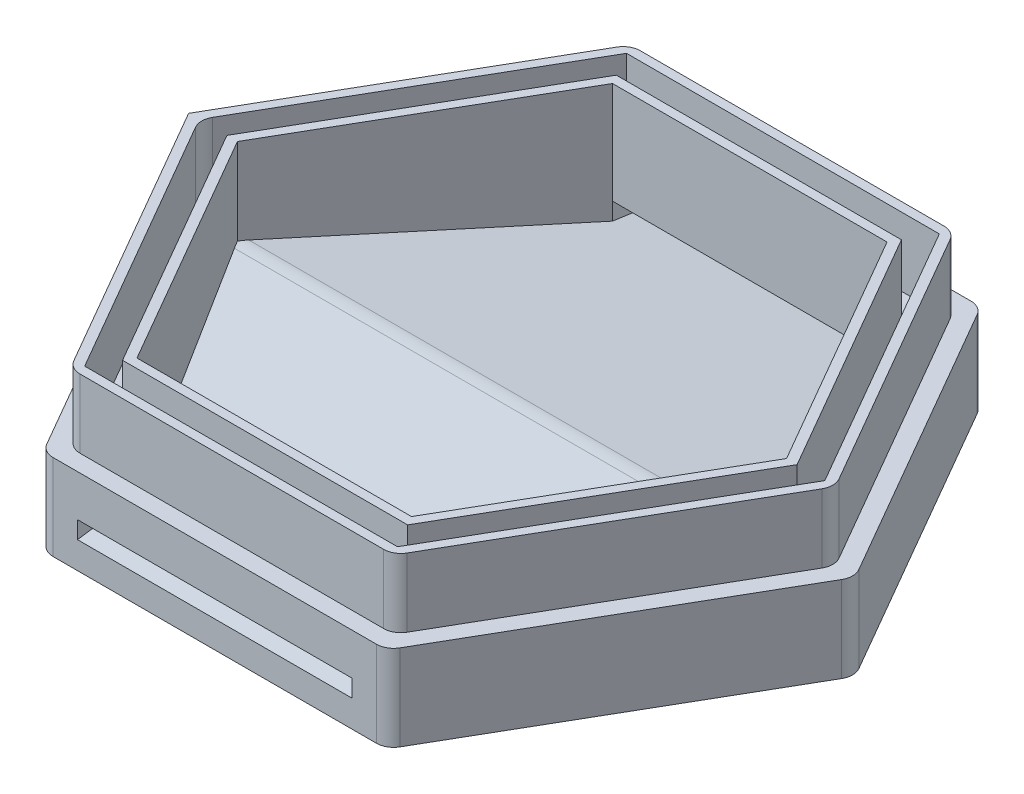
SolidWorks part; units mm, degrees
ref_plane "Front Plane" through (0, 0, 0) normal (0, 0, 1) x (1, 0, 0)
ref_plane "Top Plane" through (0, 0, 0) normal (0, 1, 0) x (1, 0, 0)
ref_plane "Right Plane" through (0, 0, 0) normal (1, 0, 0) x (0, 0, -1)
sketch "Sketch1" plane through (0, 0, 0) normal (0, 1, 0) x (1, 0, 0)
  line L1 (0, 0) -> (-50, 86.6025)
  line L2 (-50, 86.6025) -> (-150, 86.6025)
  line L3 (-150, 86.6025) -> (-200, 0)
  line L4 (-200, 0) -> (-150, -86.6025)
  line L5 (-150, -86.6025) -> (-50, -86.6025)
  line L6 (-50, -86.6025) -> (0, 0)
  dimension "200" = 200
extrude "Boss-Extrude1" add sketch "Sketch1" along normal blind 25
sketch "Sketch6" plane through (0, 25, 0) normal (0, 1, 0) x (1, 0, 0)
  line L0 (-100, -86.6025) -> (-100, 86.6025) construction
  line L3 (0, 0) -> (-200, 0) construction
  line L4 (-150, -86.6025) -> (-50, -86.6025) construction
  line L5 (-50, 86.6025) -> (-150, 86.6025) construction
  line L7 (-180, 0) -> (-140, -69.282)
  line L8 (-140, -69.282) -> (-60, -69.282)
  line L9 (-60, -69.282) -> (-20, 0)
  line L10 (-20, 0) -> (-60, 69.282)
  line L11 (-60, 69.282) -> (-140, 69.282)
  line L12 (-140, 69.282) -> (-180, 0)
  circle A0 centre (-100, 0) radius 69.282 construction
  dimension "D1" = 160
extrude "Cut-Extrude1" cut sketch "Sketch6" against normal blind 5
ref_plane "Plane3" through (0, 36.0941, 6.3644) normal (0, 0.9848, 0.1736) x (1, 0, 0)
sketch "Sketch10" plane through (0, 20, 0) normal (0, 1, 0) x (1, 0, 0)
  line L0 (-100, 69.282) -> (-100, -69.282) construction
  line L1 (-60, 69.282) -> (-140, 69.282) construction
  line L2 (-140, -69.282) -> (-60, -69.282) construction
  line L3 (-180, 0) -> (-20, 0) construction
  line L4 (-60, -69.282) -> (-140, 69.282) construction
  line L5 (-40, 34.641) -> (-160, -34.641) construction
  line L6 (-20, 0) -> (-60, 69.282) construction
  line L7 (-180, 0) -> (-140, -69.282) construction
  line L8 (-140, -69.282) -> (-60, 69.282) construction
  line L9 (-40, -34.641) -> (-160, 34.641) construction
  line L10 (-60, -69.282) -> (-20, 0) construction
  line L11 (-140, 69.282) -> (-180, 0) construction
ref_plane "Plane10" through (-100, 0, 0) normal (1, 0, 0) x (0, 0, -1)
sketch "Sketch21" plane through (-100, 0, 0) normal (1, 0, 0) x (0, 0, -1)
  line L0 (69.282, 20) -> (69.282, 10.263)
  line L2 (69.282, 10.263) -> (0, 20)
  line L3 (0, 25) -> (0, 0) construction
  line L4 (0, 0) -> (0, 20) construction
  line L5 (0, 20) -> (69.282, 20)
  line L6 (69.282, 25) -> (69.282, 20) construction
  line L7 (0, 20) -> (69.282, 20) construction
  dimension "D1" = 8
extrude "Cut-Extrude7" cut sketch "Sketch21" along normal up to surface and the other way up to surface up to face at (-40, 22.5, -34.641) other way up to face at (-160, 22.5, -34.641)
sketch "Sketch22" plane through (-100, 0, 0) normal (1, 0, 0) x (0, 0, -1)
  line L0 (0, 20) -> (-69.282, 10.263)
  line L1 (-69.282, 10.263) -> (-69.282, 20)
  line L2 (-69.282, 20) -> (0, 20)
  line L3 (69.282, 25) -> (69.282, 10.263) construction
  line L4 (69.282, 10.263) -> (69.282, 25) construction
  line L5 (69.282, 10.263) -> (-69.282, 10.263) construction
  dimension "D1" = 8
extrude "Cut-Extrude8" cut sketch "Sketch22" along normal up to surface and the other way up to surface up to face at (-40, 22.5, 34.641) other way up to face at (-160, 22.5, 34.641)
sketch "Sketch23" plane through (-100, 0, 0) normal (1, 0, 0) x (0, 0, -1)
  line L0 (69.282, 10.263) -> (89.282, 7.4522)
  line L1 (89.282, 7.4522) -> (89.282, 12.5014)
  line L2 (89.282, 12.5014) -> (69.282, 15.3122)
  line L3 (69.282, 10.263) -> (69.282, 25) construction
  line L4 (0, 20) -> (69.282, 10.263) construction
  line L5 (69.282, 15.3122) -> (69.282, 10.263)
  line L6 (0, 25) -> (0, 38.3565) construction
  line L7 (-69.282, 15.3122) -> (-69.282, 10.263)
  line L8 (-89.282, 12.5014) -> (-69.282, 15.3122)
  line L9 (-89.282, 7.4522) -> (-89.282, 12.5014)
  line L10 (-69.282, 10.263) -> (-89.282, 7.4522)
  dimension "D1" = 5
  dimension "D2" = 20
extrude "Cut-Extrude9" cut sketch "Sketch23" against normal up to vertex (40 mm away) and the other way up to vertex (40 mm away)
fillet "Fillet2" radius 15 1 edges at (-100, 20, 0)
sketch "Sketch27" plane through (0, 25, 0) normal (0, 1, 0) x (1, 0, 0)
  line L0 (0, 0) -> (-200, 0) construction
  line L1 (-100, 86.6025) -> (-100, -86.6025) construction
  line L2 (-50, 86.6025) -> (-150, 86.6025) construction
  line L3 (-150, -86.6025) -> (-50, -86.6025) construction
  line L4 (-140, 69.282) -> (-180, 0) construction
  line L5 (-10, 0) -> (-55, 77.9423) construction
  line L6 (-55, 77.9423) -> (-145, 77.9423) construction
  line L7 (-145, 77.9423) -> (-190, 0) construction
  line L8 (-190, 0) -> (-145, -77.9423) construction
  line L9 (-145, -77.9423) -> (-55, -77.9423) construction
  line L10 (-55, -77.9423) -> (-10, 0) construction
  line L23 (-15.7735, 0) -> (-57.8868, 72.9423) construction
  line L24 (-57.8868, 72.9423) -> (-142.1132, 72.9423) construction
  line L25 (-142.1132, 72.9423) -> (-184.2265, 0) construction
  line L26 (-184.2265, 0) -> (-142.1132, -72.9423) construction
  line L27 (-142.1132, -72.9423) -> (-57.8868, -72.9423) construction
  line L28 (-57.8868, -72.9423) -> (-15.7735, 0) construction
  line L29 (-150, 86.6025) -> (-200, 0) construction
  line L30 (-178.7947, 2.0876) -> (-140, 69.282) construction
  line L32 (-16.9282, 0) -> (-58.4641, 71.9423)
  line L33 (-58.4641, 71.9423) -> (-141.5359, 71.9423)
  line L34 (-141.5359, 71.9423) -> (-183.0718, 0)
  line L35 (-183.0718, 0) -> (-141.5359, -71.9423)
  line L36 (-141.5359, -71.9423) -> (-58.4641, -71.9423)
  line L37 (-58.4641, -71.9423) -> (-16.9282, 0)
  line L38 (-5.7735, 0) -> (-52.8868, 81.6025)
  line L39 (-21.2053, 2.0876) -> (-60, 69.282) construction
  line L40 (-50, -86.6025) -> (0, 0) construction
  line L41 (-20, 0) -> (-60, 69.282)
  line L42 (-60, 69.282) -> (-140, 69.282)
  line L43 (-140, 69.282) -> (-180, 0)
  line L44 (-180, 0) -> (-140, -69.282)
  line L45 (-140, -69.282) -> (-60, -69.282)
  line L46 (-60, -69.282) -> (-20, 0)
  line L47 (-8.8453, 0) -> (-54.4226, 78.9423)
  line L48 (-54.4226, 78.9423) -> (-145.5774, 78.9423)
  line L49 (-145.5774, 78.9423) -> (-191.1547, 0)
  line L50 (-191.1547, 0) -> (-145.5774, -78.9423)
  line L51 (-145.5774, -78.9423) -> (-54.4226, -78.9423)
  line L52 (-54.4226, -78.9423) -> (-8.8453, 0)
  line L53 (-52.8868, 81.6025) -> (-147.1132, 81.6025)
  line L54 (-147.1132, 81.6025) -> (-194.2265, 0)
  line L55 (-194.2265, 0) -> (-147.1132, -81.6025)
  line L56 (-147.1132, -81.6025) -> (-52.8868, -81.6025)
  line L57 (-52.8868, -81.6025) -> (-5.7735, 0)
  circle A0 centre (-100, 0) radius 77.9423 construction
  circle A1 centre (-100, 0) radius 72.9423 construction
  circle A2 centre (-100, 0) radius 71.9423 construction
  circle A3 centre (-100, 0) radius 69.282 construction
  circle A4 centre (-100, 0) radius 78.9423 construction
  circle A5 centre (-100, 0) radius 81.6025 construction
  line M20 (-180, 0) -> (-140, 69.282)
  line M21 (-140, 69.282) -> (-60, 69.282)
  line M22 (-60, 69.282) -> (-20, 0)
  line M23 (-20, 0) -> (-60, -69.282)
  line M24 (-60, -69.282) -> (-140, -69.282)
  line M25 (-140, -69.282) -> (-180, 0)
  dimension "D1" = 180
  dimension "D2" = 5
  dimension "D3" = 1
  dimension "D4" = 2.6603
  dimension "1" = 1
extrude "Boss-Extrude5" add sketch "Sketch27" along normal blind 20 contours L56 L57 L38 L53 L54 L55 L52 L51 L50 L49 L48 L47 | L36 L37 L32 L33 L34 L35 M25 M20 M21 M22 M23 M24
fillet "Fillet3" radius 5 12 edges at (-50, 12.5, -86.6025) (0, 12.5, 0) (-50, 12.5, 86.6025) (-150, 12.5, 86.6025) (-200, 12.5, 0) (-150, 12.5, -86.6025) (-52.8868, 35, -81.6025) (-147.1132, 35, -81.6025) (-191.1547, 35, 0) (-147.1132, 35, 81.6025) (-5.7735, 35, 0) (-52.8868, 35, 81.6025)
